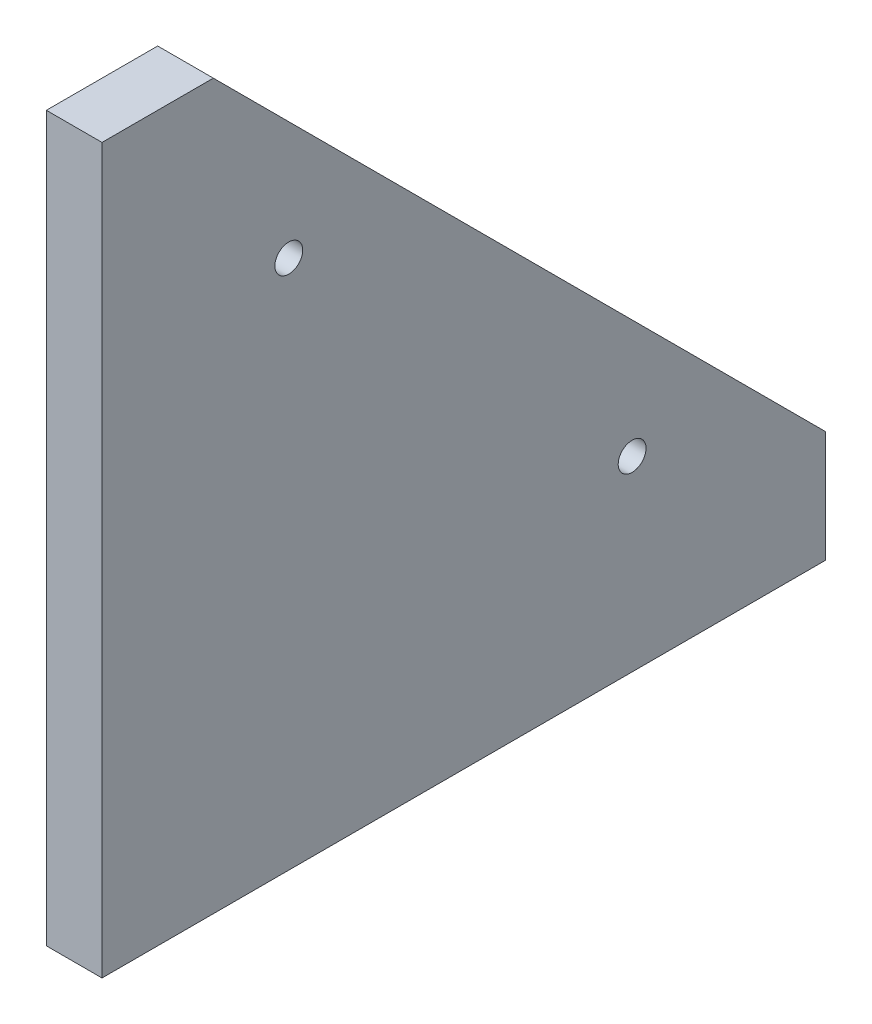
SolidWorks part; units mm, degrees
other "Connection Feature"
ref_plane "Front Plane" through (0, 0, 0) normal (0, 0, 1) x (1, 0, 0)
ref_plane "Top Plane" through (0, 0, 0) normal (0, 1, 0) x (1, 0, 0)
ref_plane "Right Plane" through (0, 0, 0) normal (1, 0, 0) x (0, 0, -1)
sketch "Sketch1" plane through (0, 0, 0) normal (1, 0, 0) x (0, 0, -1)
  line L0 (0, 65) -> (0, 0)
  line L1 (0, 0) -> (65, 0)
  line L2 (65, 0) -> (65, 10)
  line L3 (65, 10) -> (10, 65)
  line L4 (10, 65) -> (0, 65)
  line L5 (0, 0) -> (37.5, 37.5) construction
  line L6 (16.7757, 47.6177) -> (47.6177, 16.7757) construction
  point P9 (32.1967, 32.1967)
  dimension "D1" = 65
  dimension "D2" = 10
  dimension "D3" = 7.5
extrude "Boss-Extrude1" add sketch "Sketch1" along normal mid plane 5
hole_wizard "Ø2.5mm Dowel Hole1" positions "Sketch2" profile "Sketch3" hole size "Ø2.5" standard "ANSI Metric" end condition through all
sketch "Sketch2" plane through (2.5, 0, 0) normal (1, 0, 0) x (0, 0, -1)
  point P0 (16.7757, 47.6177)
  point P3 (47.6177, 16.7757)
sketch "Sketch3" plane through (2.5, 47.6177, -16.7757) normal (0, 1, 0) x (0, 0, -1)
  line L0 (0, 0) -> (0, 5)
  line L1 (0, 5) -> (1.275, 5)
  line L2 (1.25, 4.975) -> (1.25, 0)
  line L5 (1.25, 0) -> (0, 0)
  line L7 (1.275, 5) -> (1.25, 4.975)
  line L8 (-1.275, 5) -> (-1.25, 4.975) construction
  line L11 (0, -6.35) -> (0, 107.95) construction
  dimension "Thru Hole Dia." = 2.5
  dimension "Thru Hole Depth" = 5
  dimension "Far C'Sink Dia." = 2.55
  dimension "Far C'Sink Angle" = 90
other "Configuration Table"
